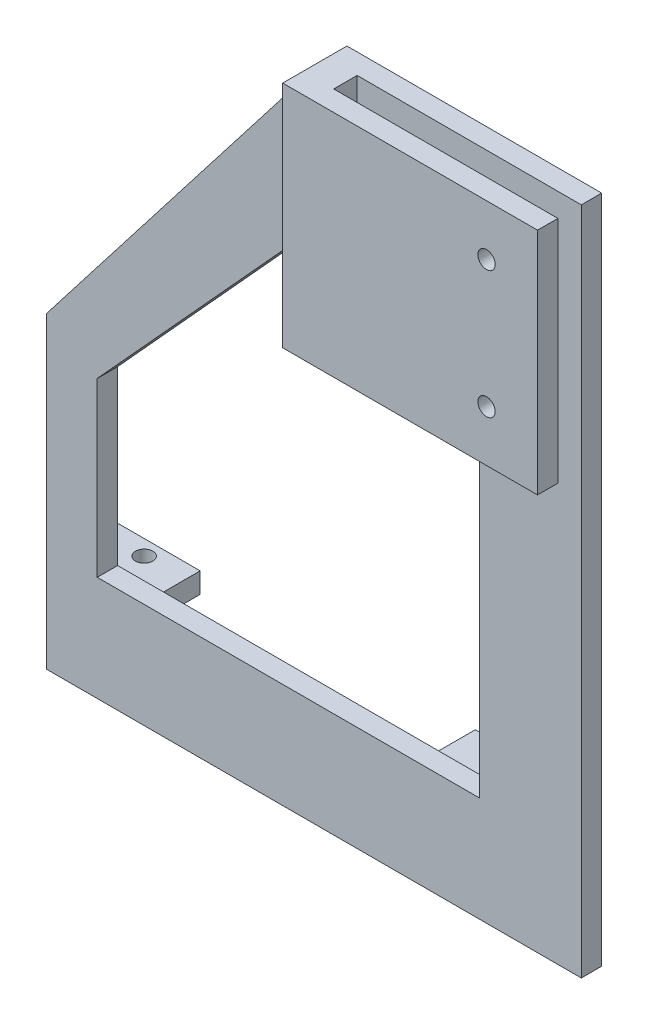
SolidWorks part; units mm, degrees
ref_plane "前视基准面" through (0, 0, 0) normal (0, 0, 1) x (1, 0, 0)
ref_plane "上视基准面" through (0, 0, 0) normal (0, 1, 0) x (1, 0, 0)
ref_plane "右视基准面" through (0, 0, 0) normal (1, 0, 0) x (0, 0, -1)
other "Configuration Table"
sketch "草图1" plane through (0, 0, 0) normal (0, 0, 1) x (1, 0, 0)
  line L0 (-65, -5.4) -> (40, -5.4)
  line L1 (40, -5.4) -> (40, 126)
  line L2 (40, 126) -> (-10, 126)
  line L3 (-10, 126) -> (-65, 55)
  line L4 (-65, 55) -> (-65, -5.4)
  dimension "D1" = 40
  dimension "D2" = 10
  dimension "D3" = 65
  dimension "D4" = 55
  dimension "D5" = 126
  dimension "D6" = 5.4
extrude "卡座外侧承力框" add sketch "草图1" along normal blind 4 from offset 0.2
sketch "草图2" plane through (0, 0, 0) normal (0, 0, 1) x (1, 0, 0)
  line L0 (-55, 15.2) -> (20, 15.2)
  line L1 (20, 15.2) -> (20, 105)
  line L2 (20, 105) -> (-4, 105)
  line L3 (-4, 105) -> (-55, 49)
  line L4 (-55, 49) -> (-55, 15.2)
  dimension "D1" = 20
  dimension "D2" = 4
  dimension "D3" = 55
  dimension "D4" = 15.2
  dimension "D5" = 49
  dimension "D6" = 105
extrude "承力框减重窗口" cut sketch "草图2" against normal through all and the other way through all
sketch "草图3" plane through (0, 0, 0) normal (0, 0, 1) x (1, 0, 0)
  line L1 (-63, 10.2) -> (-47, 10.2)
  line L2 (-63, 10.2) -> (-63, 14.2)
  line L3 (-63, 14.2) -> (-47, 14.2)
  line L4 (-47, 10.2) -> (-47, 14.2)
  line L6 (7, 10.2) -> (23, 10.2)
  line L7 (7, 10.2) -> (7, 14.2)
  line L8 (7, 14.2) -> (23, 14.2)
  line L9 (23, 10.2) -> (23, 14.2)
  dimension "D1" = 7
  dimension "D2" = 23
  dimension "D3" = 47
  dimension "D4" = 10.2
  dimension "D5" = 14.2
extrude "上卡唇" add sketch "草图3" along normal blind 12.2 from offset 8
sketch "草图4" plane through (0, 0, 0) normal (0, 0, 1) x (1, 0, 0)
  line L1 (-63, -5.4) -> (-47, -5.4)
  line L2 (-63, -5.4) -> (-63, -2.7)
  line L3 (-63, -2.7) -> (-47, -2.7)
  line L4 (-47, -5.4) -> (-47, -2.7)
  line L6 (7, -5.4) -> (23, -5.4)
  line L7 (7, -5.4) -> (7, -2.7)
  line L8 (7, -2.7) -> (23, -2.7)
  line L9 (23, -5.4) -> (23, -2.7)
  dimension "D1" = 7
  dimension "D2" = 23
  dimension "D3" = 47
  dimension "D4" = 2.7
  dimension "D5" = 5.4
extrude "下卡唇螺母承力底" add sketch "草图4" along normal blind 14.2 from offset 10
sketch "草图5" plane through (0, 0, 0) normal (0, 1, 0) x (1, 0, 0)
  line L1 (-63, -4.2) -> (-47, -4.2)
  line L2 (-63, -4.2) -> (-63, 10)
  line L3 (-63, 10) -> (-47, 10)
  line L4 (-47, -4.2) -> (-47, 10)
  line L6 (-58.35, 2.1) -> (-51.65, 2.1)
  line L7 (-58.35, 2.1) -> (-58.35, 7.9)
  line L8 (-58.35, 7.9) -> (-51.65, 7.9)
  line L9 (-51.65, 2.1) -> (-51.65, 7.9)
  line L11 (7, -4.2) -> (23, -4.2)
  line L12 (7, -4.2) -> (7, 10)
  line L13 (7, 10) -> (23, 10)
  line L14 (23, -4.2) -> (23, 10)
  line L16 (11.65, 2.1) -> (18.35, 2.1)
  line L17 (11.65, 2.1) -> (11.65, 7.9)
  line L18 (11.65, 7.9) -> (18.35, 7.9)
  line L19 (18.35, 2.1) -> (18.35, 7.9)
  dimension "D1" = 7
  dimension "D2" = 11.65
  dimension "D3" = 18.35
  dimension "D4" = 23
  dimension "D5" = 47
  dimension "D6" = 51.65
  dimension "D7" = 2.1
  dimension "D8" = 7.9
  dimension "D9" = 10
  dimension "D10" = 4.2
extrude "下卡唇M3螺母防转槽" add sketch "草图5" along normal blind 2.5 from offset 2.7
sketch "草图6" plane through (0, 0, 0) normal (0, 0, 1) x (1, 0, 0)
  line L1 (-10, 81) -> (-4, 81)
  line L2 (-10, 81) -> (-10, 126)
  line L3 (-10, 126) -> (-4, 126)
  line L4 (-4, 81) -> (-4, 126)
  dimension "D1" = 4
  dimension "D2" = 10
  dimension "D3" = 81
  dimension "D4" = 126
extrude "梁根后挡" add sketch "草图6" along normal blind 12.6 from offset 0.2
sketch "草图7" plane through (0, 0, 0) normal (0, 0, 1) x (1, 0, 0)
  line L1 (-10, 81) -> (40, 81)
  line L2 (-10, 81) -> (-10, 126)
  line L3 (-10, 126) -> (40, 126)
  line L4 (40, 81) -> (40, 126)
  dimension "D1" = 40
  dimension "D2" = 10
  dimension "D3" = 81
  dimension "D4" = 126
extrude "梁根外夹片" add sketch "草图7" along normal blind 4 from offset 8.8
sketch "草图8" plane through (0, 0, 0) normal (0, 0, 1) x (1, 0, 0)
  circle A0 centre (30, 91) radius 1.7
  circle A1 centre (30, 116) radius 1.7
  dimension "D1" = 3.4
  dimension "D2" = 30
  dimension "D3" = 91
  dimension "D4" = 116
extrude "梁根两孔3p4" cut sketch "草图8" against normal through all and the other way through all
sketch "草图9" plane through (0, 0, 0) normal (0, 1, 0) x (1, 0, 0)
  circle A0 centre (-55, 5) radius 1.7
  circle A1 centre (15, 5) radius 1.7
  dimension "D1" = 3.4
  dimension "D2" = 15
  dimension "D3" = 55
  dimension "D4" = 5
extrude "板边压紧孔3p4" cut sketch "草图9" against normal through all and the other way through all
